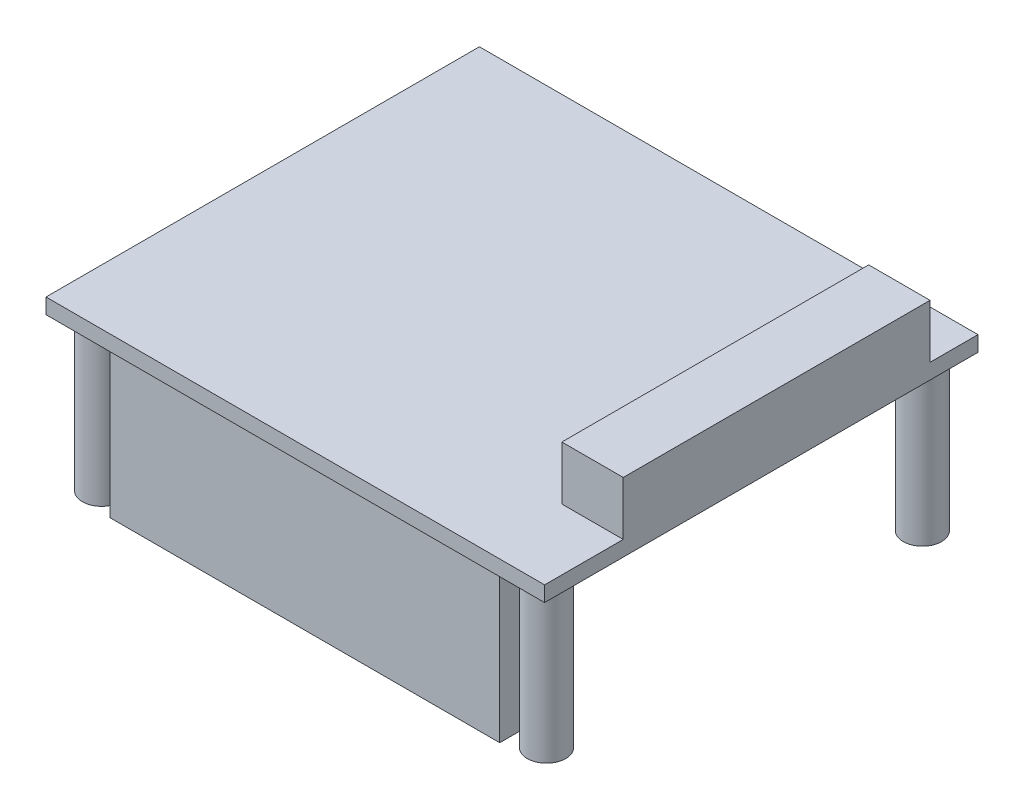
SolidWorks part; units mm, degrees
ref_plane "Front Plane" through (0, 0, 0) normal (0, 0, 1) x (1, 0, 0)
ref_plane "Top Plane" through (0, 0, 0) normal (0, 1, 0) x (1, 0, 0)
ref_plane "Right Plane" through (0, 0, 0) normal (1, 0, 0) x (0, 0, -1)
sketch "SK_P01_Standoff" plane through (0, 0, 0) normal (0, 1, 0) x (1, 0, 0)
  circle A0 centre (-29, 24.5) radius 2.5
extrude "P01_Standoff" add sketch "SK_P01_Standoff" along normal blind 20
sketch "SK_P02_Standoff" plane through (0, 0, 0) normal (0, 1, 0) x (1, 0, 0)
  circle A0 centre (-29, -24.5) radius 2.5
extrude "P02_Standoff" add sketch "SK_P02_Standoff" along normal blind 20
sketch "SK_P03_Standoff" plane through (0, 0, 0) normal (0, 1, 0) x (1, 0, 0)
  circle A0 centre (29, 24.5) radius 2.5
extrude "P03_Standoff" add sketch "SK_P03_Standoff" along normal blind 20
sketch "SK_P04_Standoff" plane through (0, 0, 0) normal (0, 1, 0) x (1, 0, 0)
  circle A0 centre (29, -24.5) radius 2.5
extrude "P04_Standoff" add sketch "SK_P04_Standoff" along normal blind 20
sketch "SK_P05_PermaProtoHAT35mmfancuto" plane through (0, 0, 0) normal (0, 1, 0) x (1, 0, 0)
  line L0 (-32.5, -28.25) -> (32.5, -28.25)
  line L1 (32.5, -28.25) -> (32.5, 28.25)
  line L2 (32.5, 28.25) -> (-32.5, 28.25)
  line L3 (-32.5, 28.25) -> (-32.5, -28.25)
extrude "P05_PermaProtoHAT35mmfancuto" add sketch "SK_P05_PermaProtoHAT35mmfancuto" along normal blind 2 from offset 20
sketch "SK_P06_Stackingheader" plane through (0, 0, 0) normal (0, 1, 0) x (1, 0, 0)
  line L0 (-25.4, -27) -> (25.4, -27)
  line L1 (25.4, -27) -> (25.4, -22)
  line L2 (25.4, -22) -> (-25.4, -22)
  line L3 (-25.4, -22) -> (-25.4, -27)
extrude "P06_Stackingheader" add sketch "SK_P06_Stackingheader" along normal blind 20
sketch "SK_P07_JSTXHheadersvertical" plane through (0, 0, 0) normal (0, 1, 0) x (1, 0, 0)
  line L0 (24.5, -18) -> (32.5, -18)
  line L1 (32.5, -18) -> (32.5, 22)
  line L2 (32.5, 22) -> (24.5, 22)
  line L3 (24.5, 22) -> (24.5, -18)
extrude "P07_JSTXHheadersvertical" add sketch "SK_P07_JSTXHheadersvertical" along normal blind 7 from offset 22
